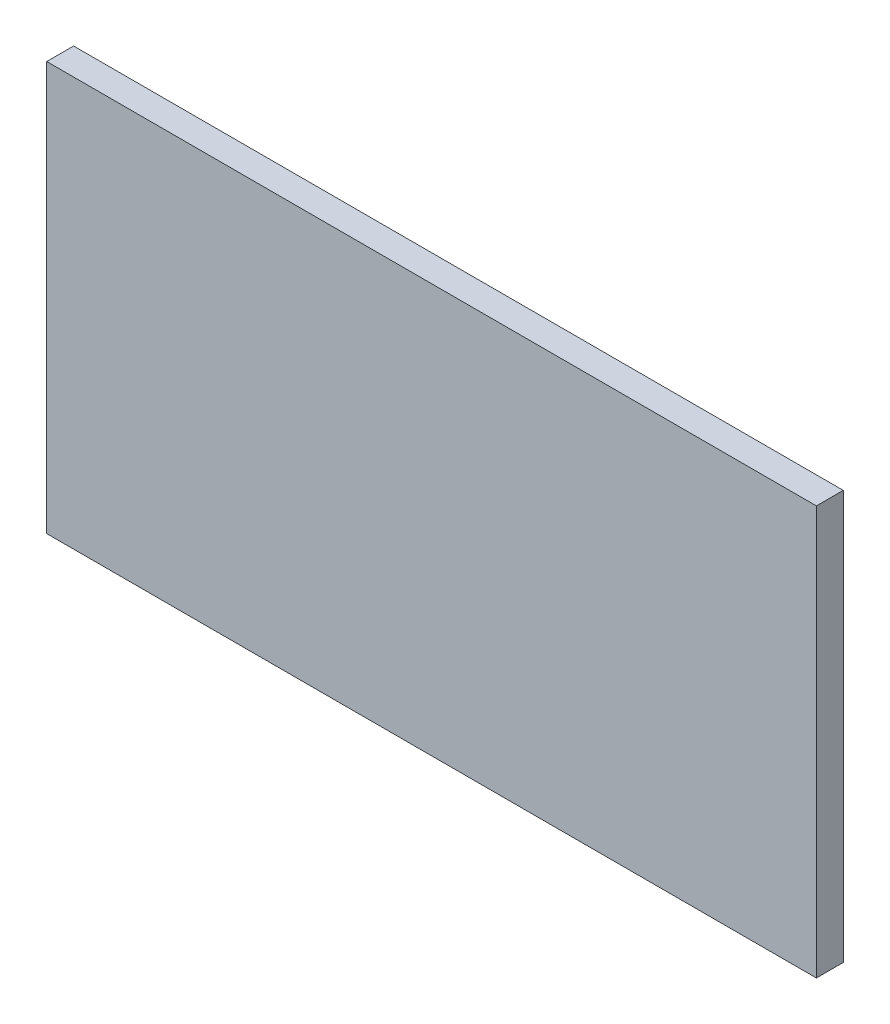
SolidWorks part; units mm, degrees
ref_plane "Front Plane" through (0, 0, 0) normal (0, 0, 1) x (1, 0, 0)
ref_plane "Top Plane" through (0, 0, 0) normal (0, 1, 0) x (1, 0, 0)
ref_plane "Right Plane" through (0, 0, 0) normal (1, 0, 0) x (0, 0, -1)
sketch "Sketch1" plane through (0, 0, 0) normal (0, 0, 1) x (1, 0, 0)
  line L1 (143.2371, 76.0947) -> (-143.2371, 76.0947)
  line L2 (143.2371, 76.0947) -> (143.2371, -76.0947)
  line L3 (143.2371, -76.0947) -> (-143.2371, -76.0947)
  line L4 (-143.2371, 76.0947) -> (-143.2371, -76.0947)
  line L5 (143.2371, 76.0947) -> (-143.2371, -76.0947) construction
  line L6 (143.2371, -76.0947) -> (-143.2371, 76.0947) construction
  point P0 (0, 0)
extrude "Boss-Extrude1" add sketch "Sketch1" along normal blind 10
sketch "Sketch2" plane through (0, 0, 10) normal (0, 0, 1) x (1, 0, 0)
  line L0 (143.2371, -76.0947) -> (143.2371, 76.0947) construction
  line L1 (-143.2371, -76.0947) -> (143.2371, -76.0947) construction
  arc A0 (0, 0) -> (-37.0868, -36.0051) centre (-45.1645, 9.4183) cw
  arc A1 (0, 0) -> (143.2371, 43.7315) centre (83.6181, -17.4371) cw
  arc A2 (-37.0868, -36.0051) -> (-81.282, -76.0947) centre (-27.2646, -91.2385) ccw
